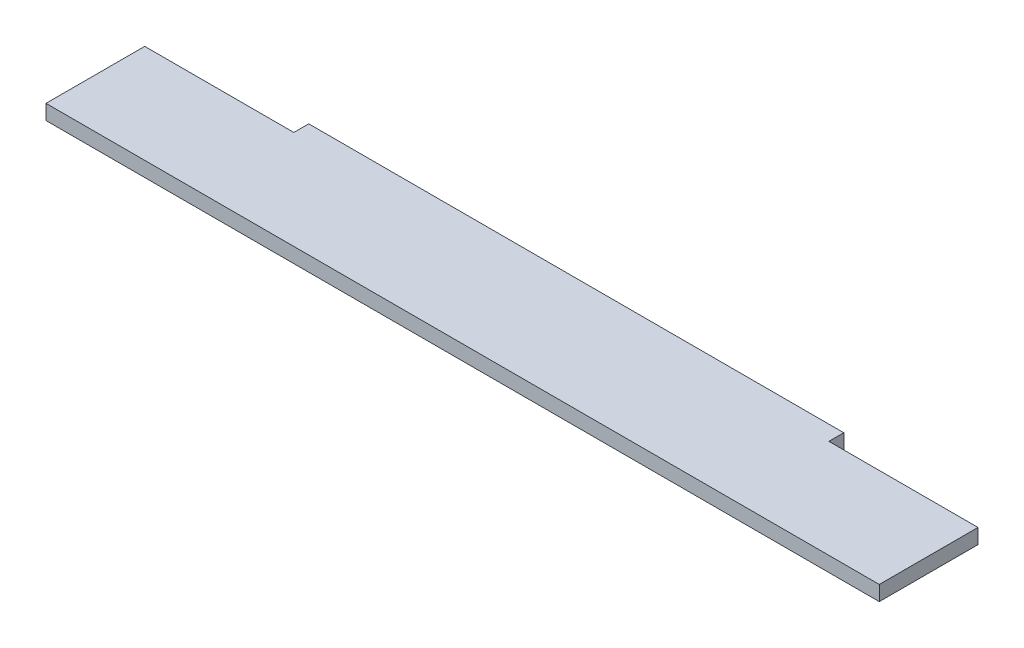
SolidWorks part; units mm, degrees
ref_plane "Front Plane" through (0, 0, 0) normal (0, 0, 1) x (1, 0, 0)
ref_plane "Top Plane" through (0, 0, 0) normal (0, 1, 0) x (1, 0, 0)
ref_plane "Right Plane" through (0, 0, 0) normal (1, 0, 0) x (0, 0, -1)
sketch "Sketch1" plane through (0, 0, 0) normal (0, 1, 0) x (1, 0, 0)
  line L0 (-139.7, -33.1) -> (-139.7, 0)
  line L1 (-139.7, 0) -> (-89.7, 0)
  line L2 (-89.7, 0) -> (-89.7, 5)
  line L3 (-89.7, 5) -> (89.7, 5)
  line L4 (89.7, 5) -> (89.7, 0)
  line L5 (89.7, 0) -> (139.7, 0)
  line L6 (139.7, 0) -> (139.7, -33.1)
  line L7 (139.7, -33.1) -> (-139.7, -33.1)
  line L8 (0, 35.7281) -> (0, 0) construction
  line L9 (0, 0) -> (40.8322, 0) construction
  dimension "D1" = 279.4
  dimension "D2" = 50
  dimension "D3" = 179.4
  dimension "D4" = 38.1
  dimension "D5" = 5
extrude "Boss-Extrude1" add sketch "Sketch1" along normal blind 5
